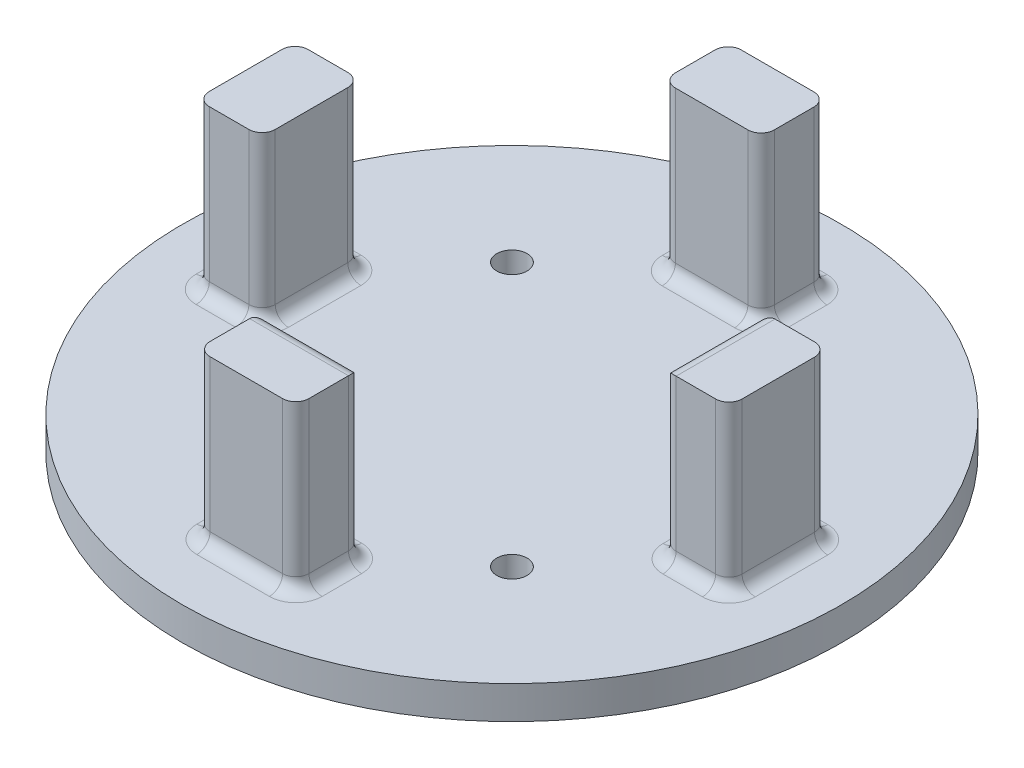
SolidWorks part; units mm, degrees
ref_plane "Front Plane" through (0, 0, 0) normal (0, 0, 1) x (1, 0, 0)
ref_plane "Top Plane" through (0, 0, 0) normal (0, 1, 0) x (1, 0, 0)
ref_plane "Right Plane" through (0, 0, 0) normal (1, 0, 0) x (0, 0, -1)
sketch "Sketch2" plane through (0, 0, 0) normal (0, 1, 0) x (1, 0, 0)
  line L1 (-25.4, 25.4) -> (25.4, 25.4) construction
  line L2 (-25.4, 25.4) -> (-25.4, -25.4) construction
  line L3 (-25.4, -25.4) -> (25.4, -25.4) construction
  line L4 (25.4, 25.4) -> (25.4, -25.4) construction
  line L5 (-25.4, 25.4) -> (25.4, -25.4) construction
  line L6 (-25.4, -25.4) -> (25.4, 25.4) construction
  circle A0 centre (0, 0) radius 63.5
  circle A1 centre (-25.4, 25.4) radius 2.921
  circle A2 centre (25.4, 25.4) radius 2.921
  circle A3 centre (25.4, -25.4) radius 2.921
  circle A4 centre (-25.4, -25.4) radius 2.921
  dimension "D1" = 127
  dimension "D3" = 5.842
  dimension "D2" = 50.8
extrude "Boss-Extrude2" add sketch "Sketch2" along normal blind 6.35
sketch "Sketch3" plane through (0, 6.35, 0) normal (0, 1, 0) x (1, 0, 0)
  line L0 (-3.4925, 0) -> (3.4925, 0) construction
  line L1 (-44.9715, 44.831) -> (44.9715, 44.831) construction
  line L2 (-44.9715, 44.831) -> (-44.9715, -44.831) construction
  line L3 (-44.9715, -44.831) -> (44.9715, -44.831) construction
  line L4 (44.9715, 44.831) -> (44.9715, -44.831) construction
  line L5 (-44.9715, 44.831) -> (44.9715, -44.831) construction
  line L6 (-44.9715, -44.831) -> (44.9715, 44.831) construction
  line L7 (-9.525, 38.481) -> (9.525, 38.481)
  line L8 (-9.525, 38.481) -> (-9.525, 51.181)
  line L9 (-9.525, 51.181) -> (9.525, 51.181)
  line L10 (9.525, 38.481) -> (9.525, 51.181)
  line L11 (-9.525, 38.481) -> (9.525, 51.181) construction
  line L12 (-9.525, 51.181) -> (9.525, 38.481) construction
  line L13 (-9.525, -51.181) -> (9.525, -51.181)
  line L14 (9.525, -38.481) -> (9.525, -51.181)
  line L15 (-9.525, -38.481) -> (9.525, -38.481)
  line L16 (-9.525, -38.481) -> (-9.525, -51.181)
  line L17 (-9.525, -51.181) -> (9.525, -38.481) construction
  line L18 (-9.525, -38.481) -> (9.525, -51.181) construction
  line L19 (0, -3.4925) -> (0, 3.4925) construction
  line L20 (-51.3215, 9.525) -> (-38.6215, 9.525)
  line L21 (-51.3215, 9.525) -> (-51.3215, -9.525)
  line L22 (-51.3215, -9.525) -> (-38.6215, -9.525)
  line L23 (-38.6215, 9.525) -> (-38.6215, -9.525)
  line L24 (-51.3215, 9.525) -> (-38.6215, -9.525) construction
  line L25 (-51.3215, -9.525) -> (-38.6215, 9.525) construction
  line L26 (38.6215, 9.525) -> (38.6215, -9.525)
  line L27 (51.3215, -9.525) -> (38.6215, -9.525)
  line L28 (51.3215, 9.525) -> (51.3215, -9.525)
  line L29 (51.3215, 9.525) -> (38.6215, 9.525)
  circle A0 centre (0, 0) radius 63.5 construction
  circle A1 centre (0, 0) radius 63.5 construction
  point P0 (0, 0)
  point P8 (0, 44.831)
  point P19 (0, -44.831)
  point P20 (-44.9715, 0)
  point P31 (-46.7292, 42.9957)
  dimension "D1" = 12.7
  dimension "D2" = 19.05
  dimension "D3" = 89.662
extrude "Boss-Extrude3" add sketch "Sketch3" along normal blind 31.75
sketch "Sketch4" plane through (0, 38.1, 0) normal (0, 1, 0) x (1, 0, 0)
  circle A0 centre (0, 0) radius 44.45
  circle A1 centre (0, 0) radius 48.26
  dimension "D1" = 88.9
  dimension "D2" = 3.81
fillet "Fillet1" radius 2.54 34 edges at (51.3215, 6.35, 0) (44.9715, 6.35, -9.525) (44.9715, 6.35, 9.525) (38.6215, 22.225, -9.525) (38.6215, 38.1, 0) (38.6215, 22.225, 9.525) (38.6215, 6.35, 0) (51.3215, 22.225, 9.525) (51.3215, 22.225, -9.525) (-51.3215, 22.225, -9.525) (-51.3215, 22.225, 9.525) (-38.6215, 22.225, 9.525) (-38.6215, 22.225, -9.525) (9.525, 22.225, 51.181) (9.525, 22.225, 38.481) (-9.525, 22.225, 38.481) (-9.525, 22.225, 51.181) (9.525, 22.225, -38.481) (-9.525, 22.225, -38.481) (9.525, 22.225, -51.181) (-9.525, 22.225, -51.181) (0, 6.35, 51.181) (-44.9715, 6.35, 9.525) (0, 6.35, -38.481) (9.525, 6.35, 44.831) (-9.525, 6.35, 44.831) (-38.6215, 6.35, 0) (-51.3215, 6.35, 0) (9.525, 6.35, -44.831) (-9.525, 6.35, -44.831) (0, 38.1, 38.481) (0, 6.35, 38.481) (-44.9715, 6.35, -9.525) (0, 6.35, -51.181)
